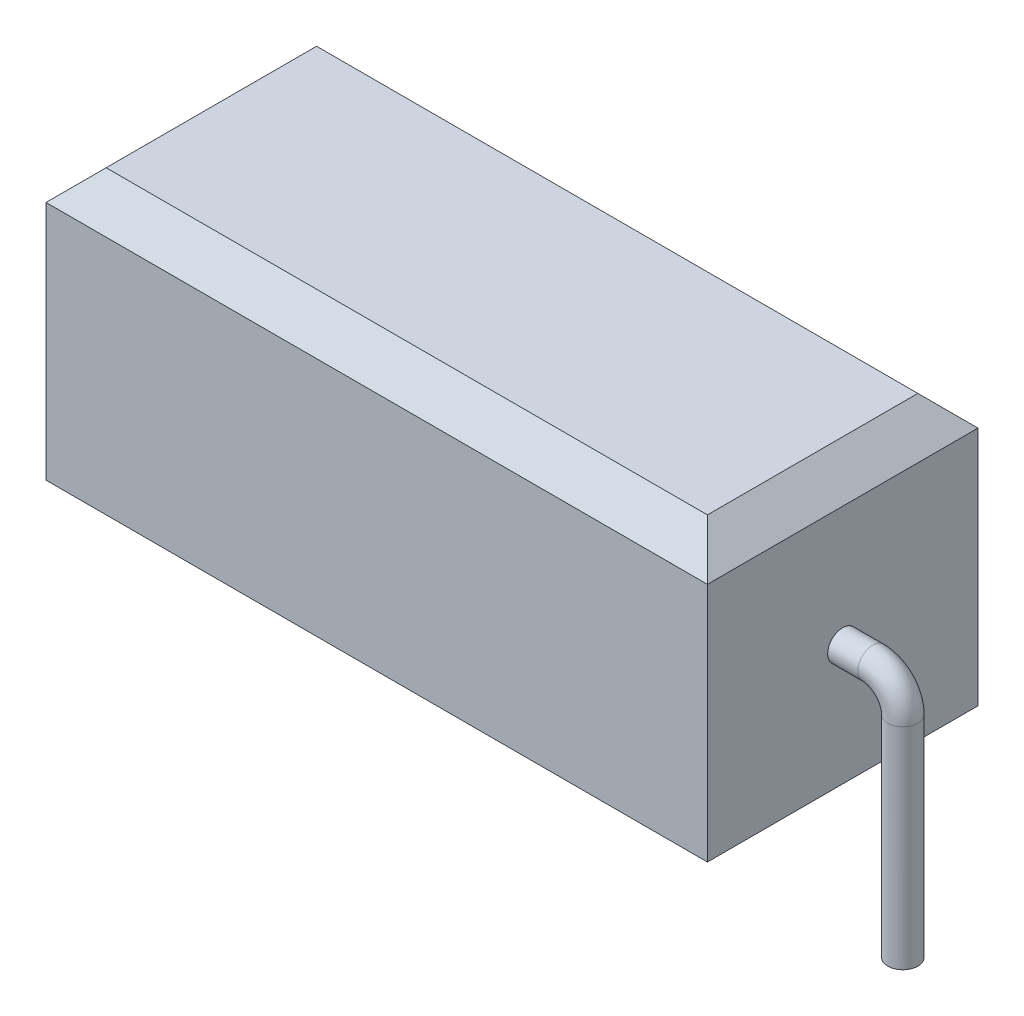
SolidWorks part; units mm, degrees
ref_plane "前视基准面" through (0, 0, 0) normal (0, 0, 1) x (1, 0, 0)
ref_plane "上视基准面" through (0, 0, 0) normal (0, 1, 0) x (1, 0, 0)
ref_plane "右视基准面" through (0, 0, 0) normal (1, 0, 0) x (0, 0, -1)
sketch "草图1" plane through (0, 0, 0) normal (0, 1, 0) x (1, 0, 0)
  line L1 (-11, -4.5) -> (11, -4.5)
  line L2 (-11, -4.5) -> (-11, 4.5)
  line L3 (-11, 4.5) -> (11, 4.5)
  line L4 (11, -4.5) -> (11, 4.5)
  line L5 (-11, -4.5) -> (11, 4.5) construction
  line L6 (-11, 4.5) -> (11, -4.5) construction
  point P0 (0, 0)
  dimension "D1" = 22
  dimension "D2" = 9
extrude "凸台-拉伸1" add sketch "草图1" along normal mid plane 10
chamfer "倒角1" distance 1 angle 45 8 edges at (0, -5, -4.5) (-11, -5, 0) (0, -5, 4.5) (11, -5, 0) (0, 5, 4.5) (-11, 5, 0) (0, 5, -4.5) (11, 5, 0)
sketch "草图2" plane through (0, 0, 0) normal (0, 0, 1) x (1, 0, 0)
  line L0 (11, 0) -> (12, 0)
  line L1 (11, 4) -> (11, -4) construction
  line L2 (13, -1) -> (13, -8)
  arc A0 (12, 0) -> (13, -1) centre (12, -1) cw
  point P8 (13, 0)
  dimension "D3" = 1
  dimension "D1" = 2
  dimension "D2" = 8
sweep "扫描1" add path "草图2" circular profile diameter 1 parameters "D3"=1
sketch "草图9" plane through (0, 0, 0) normal (0, 0, 1) x (1, 0, 0)
  line L0 (-11, 0) -> (-12, 0)
  line L1 (-11, 4) -> (-11, -4) construction
  line L2 (-13, -1) -> (-13, -8)
  arc A0 (-12, 0) -> (-13, -1) centre (-12, -1) ccw
  point P8 (-13, 0)
  dimension "D3" = 1
  dimension "D1" = 2
  dimension "D2" = 8
sweep "扫描2" add path "草图9" circular profile diameter 1 parameters "D3"=1
sketch "草图14" plane through (0, -8, 0) normal (0, -1, 0) x (-1, 0, 0)
  point P0 (13, 0)
  point P1 (-13, 0)
  dimension "D1" = 26
